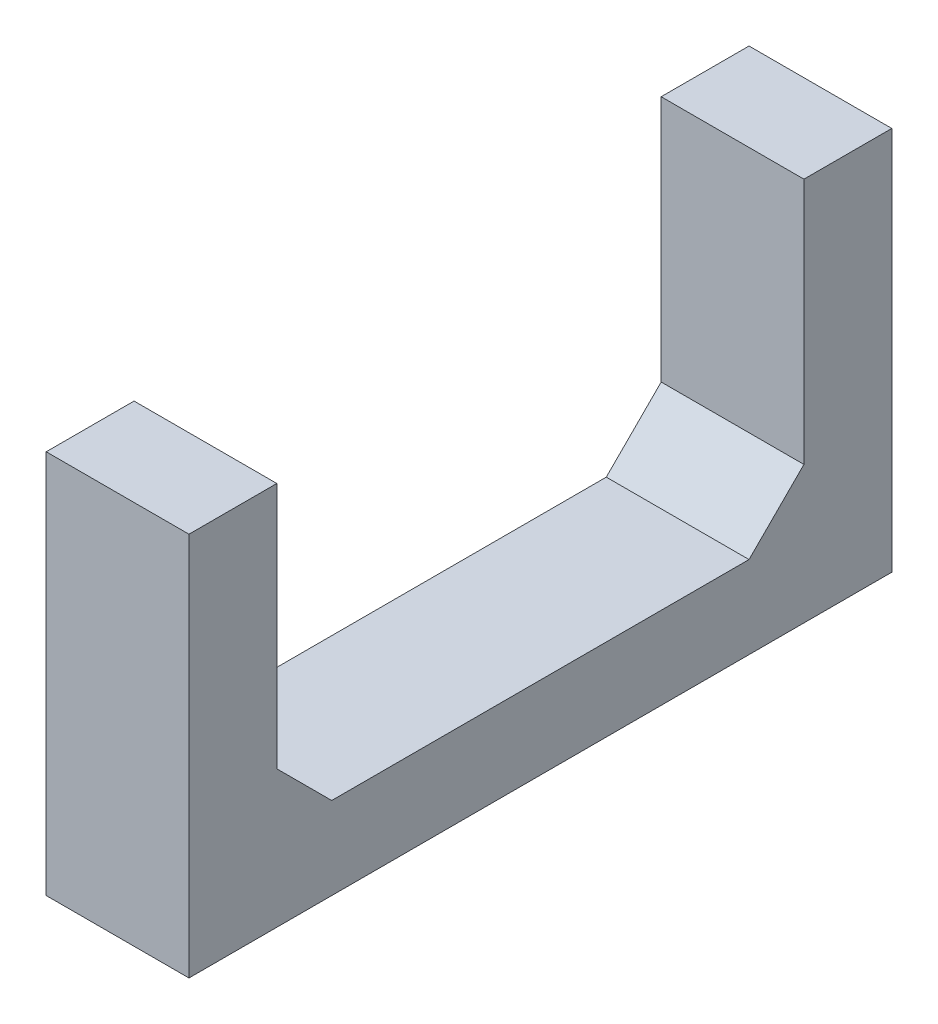
SolidWorks part; units mm, degrees
ref_plane "Front Plane" through (0, 0, 0) normal (0, 0, 1) x (1, 0, 0)
ref_plane "Top Plane" through (0, 0, 0) normal (0, 1, 0) x (1, 0, 0)
ref_plane "Right Plane" through (0, 0, 0) normal (1, 0, 0) x (0, 0, -1)
sketch "Sketch1" plane through (0, 0, 0) normal (1, 0, 0) x (0, 0, -1)
  line L0 (0, 0) -> (0, 70)
  line L1 (0, 70) -> (16, 70)
  line L2 (16, 70) -> (16, 15)
  line L3 (16, 15) -> (112, 15)
  line L4 (112, 15) -> (112, 70)
  line L5 (112, 70) -> (128, 70)
  line L6 (128, 70) -> (128, 0)
  line L7 (128, 0) -> (0, 0)
  dimension "D1" = 96
  dimension "D2" = 16
  dimension "D3" = 16
  dimension "D4" = 55
  dimension "D5" = 15
  dimension "D6" = 55
extrude "Boss-Extrude1" add sketch "Sketch1" along normal blind 26
chamfer "Chamfer1" distance 10 angle 45 2 edges at (13, 15, -112) (13, 15, -16)
